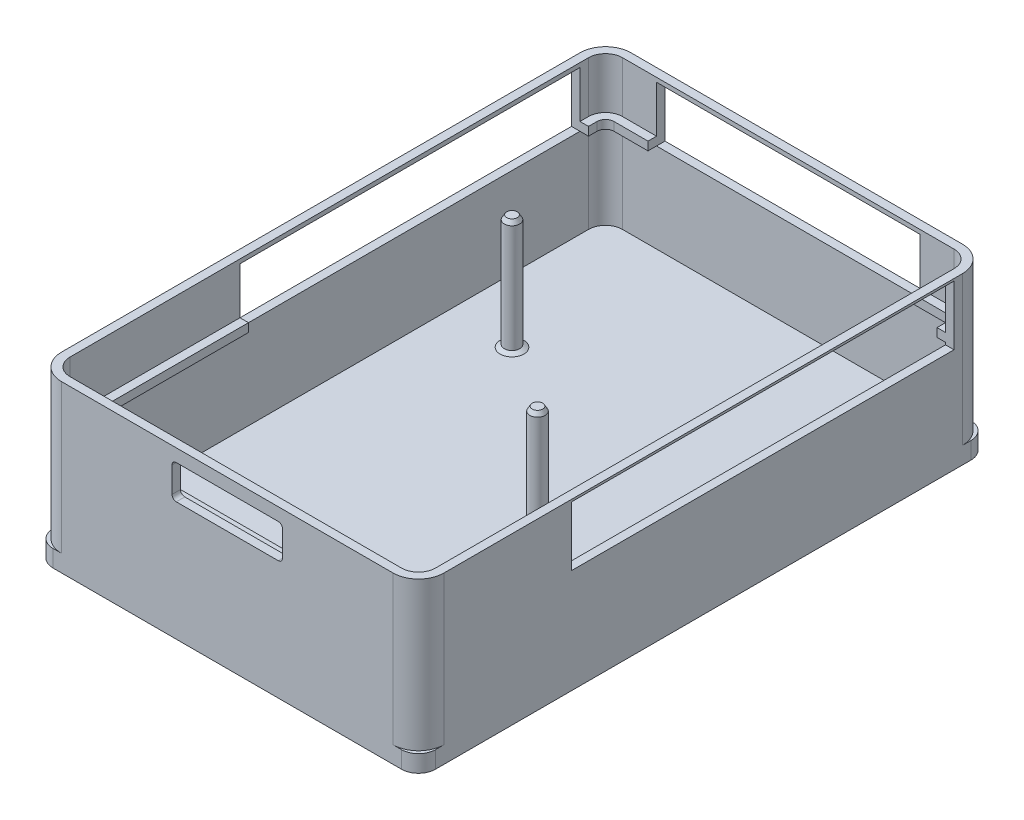
SolidWorks part; units mm, degrees
ref_plane "前视基准面" through (0, 0, 0) normal (0, 0, 1) x (1, 0, 0)
ref_plane "上视基准面" through (0, 0, 0) normal (0, 1, 0) x (1, 0, 0)
ref_plane "右视基准面" through (0, 0, 0) normal (1, 0, 0) x (0, 0, -1)
sketch "草图1" plane through (0, 0, 0) normal (0, 1, 0) x (1, 0, 0)
  line L0 (-22.5, 31.5) -> (-22.5, -31.5)
  line L1 (-20.5, -33.5) -> (20.5, -33.5)
  line L2 (22.5, -31.5) -> (22.5, 31.5)
  line L3 (20.5, 33.5) -> (-20.5, 33.5)
  arc A0 (-22.5, 31.5) -> (-20.5, 33.5) centre (-20.5, 31.5) cw
  arc A1 (22.5, 31.5) -> (20.5, 33.5) centre (20.5, 31.5) ccw
  arc A2 (-20.5, -33.5) -> (-22.5, -31.5) centre (-20.5, -31.5) cw
  arc A3 (20.5, -33.5) -> (22.5, -31.5) centre (20.5, -31.5) ccw
  point P7 (-0.3452, -0.9781)
  point P8 (0, -1.3233)
  point P9 (-22.5, 33.5)
  point P12 (22.5, 33.5)
  point P17 (22.5, -33.5)
  dimension "D5" = 2
  dimension "D6" = 2
  dimension "D7" = 2
  dimension "D8" = 2
  dimension "D1" = 45
  dimension "D2" = 67
  dimension "D3" = 33.5
  dimension "D4" = 22.5
extrude "凸台-拉伸1" add sketch "草图1" along normal blind 2
ref_plane "基准面1" through (0, 2, 0) normal (0, 1, 0) x (1, 0, 0)
sketch "草图2" plane through (0, 2, 0) normal (0, 1, 0) x (1, 0, 0)
  line L0 (-21.5, 30.5) -> (-21.5, -30.5)
  line L1 (-19.5, -32.5) -> (19.5, -32.5)
  line L2 (21.5, -30.5) -> (21.5, 30.5)
  line L3 (19.5, 32.5) -> (-19.5, 32.5)
  line L4 (19.5, 33.5) -> (-19.5, 33.5)
  line L5 (-22.5, 30.5) -> (-22.5, -30.5)
  line L6 (-19.5, -33.5) -> (19.5, -33.5)
  line L7 (22.5, -30.5) -> (22.5, 30.5)
  arc A0 (-21.5, 30.5) -> (-19.5, 32.5) centre (-19.5, 30.5) cw
  arc A1 (-19.5, -32.5) -> (-21.5, -30.5) centre (-19.5, -30.5) cw
  arc A2 (19.5, -32.5) -> (21.5, -30.5) centre (19.5, -30.5) ccw
  arc A3 (21.5, 30.5) -> (19.5, 32.5) centre (19.5, 30.5) ccw
  arc A4 (-22.5, 30.5) -> (-19.5, 33.5) centre (-19.5, 30.5) cw
  arc A5 (-19.5, -33.5) -> (-22.5, -30.5) centre (-19.5, -30.5) cw
  arc A6 (19.5, -33.5) -> (22.5, -30.5) centre (19.5, -30.5) ccw
  arc A7 (22.5, 30.5) -> (19.5, 33.5) centre (19.5, 30.5) ccw
  point P7 (-21.5, 32.5)
  point P12 (21.5, -32.5)
  point P15 (21.5, 32.5)
  dimension "D5" = 2
  dimension "D6" = 2
  dimension "D1" = 43
  dimension "D2" = 65
  dimension "D3" = 32.5
  dimension "D4" = 21.5
  dimension "D7" = 1
extrude "凸台-拉伸2" add sketch "草图2" along normal blind 17.5
sketch "草图3" plane through (0, 2, 0) normal (0, 1, 0) x (1, 0, 0)
  circle A0 centre (-14, 14) radius 0.9
  circle A1 centre (7, -4) radius 0.9
  circle A2 centre (-19, -30) radius 0.9
  point P6 (0, 0)
  point P9 (-12.6689, 9.1344)
  dimension "D3" = 1.8
  dimension "D4" = 1.8
  dimension "D7" = 1.8
  dimension "D1" = 14
  dimension "D2" = 14
  dimension "D5" = 7
  dimension "D6" = 4
  dimension "D8" = 19
  dimension "D9" = 30
extrude "凸台-拉伸3" add sketch "草图3" along normal blind 13.5
chamfer "倒角2" distance 0.5 angle 30 2 edges at (-14, 2, -14.9) (-14, 15.5, -13.1)
chamfer "倒角3" distance 0.5 angle 30 2 edges at (7, 2, 3.1) (7, 15.5, 4.9)
chamfer "倒角4" distance 0.5 angle 30 2 edges at (-19, 2, 29.1) (-19, 15.5, 30.9)
ref_plane "基准面2" through (0, 0, 33.5) normal (0, 0, 1) x (1, 0, 0)
sketch "草图4" plane through (0, 0, 33.5) normal (0, 0, 1) x (1, 0, 0)
  line L0 (-6.5, 17.5) -> (-6.5, 14.5)
  line L1 (-6, 14) -> (6, 14)
  line L2 (6.5, 14.5) -> (6.5, 17.5)
  line L3 (6, 18) -> (-6, 18)
  line L8 (-19.5, 19.5) -> (-19.5, 2) construction
  line L9 (19.5, 19.5) -> (19.5, 2) construction
  line L10 (-19.5, 19.5) -> (19.5, 19.5) construction
  arc A0 (6.5, 17.5) -> (6, 18) centre (6, 17.5) ccw
  arc A1 (6, 14) -> (6.5, 14.5) centre (6, 14.5) ccw
  arc A2 (-6, 14) -> (-6.5, 14.5) centre (-6, 14.5) cw
  arc A3 (-6.5, 17.5) -> (-6, 18) centre (-6, 17.5) cw
  point P12 (6.5, 18)
  point P15 (6.5, 14)
  dimension "D5" = 0.5
  dimension "D1" = 13
  dimension "D2" = 13
  dimension "D3" = 1.5
  dimension "D4" = 4
ref_plane "基准面4" through (0, 12.5, 0) normal (0, 1, 0) x (1, 0, 0)
sketch "草图6" plane through (0, 12.5, 0) normal (0, 1, 0) x (1, 0, 0)
  line L0 (-21.5, 30.5) -> (-21.5, -30.5)
  line L1 (-19.5, -32.5) -> (19.5, -32.5)
  line L2 (21.5, -30.5) -> (21.5, 30.5)
  line L3 (19.5, 32.5) -> (-19.5, 32.5)
  line L4 (19.5, 31.5) -> (-19.5, 31.5)
  line L5 (-20.5, 30.5) -> (-20.5, -30.5)
  line L6 (-19.5, -31.5) -> (19.5, -31.5)
  line L7 (20.5, -30.5) -> (20.5, 30.5)
  arc A0 (-21.5, 30.5) -> (-19.5, 32.5) centre (-19.5, 30.5) cw
  arc A1 (-19.5, -32.5) -> (-21.5, -30.5) centre (-19.5, -30.5) cw
  arc A2 (19.5, -32.5) -> (21.5, -30.5) centre (19.5, -30.5) ccw
  arc A3 (21.5, 30.5) -> (19.5, 32.5) centre (19.5, 30.5) ccw
  arc A4 (-20.5, 30.5) -> (-19.5, 31.5) centre (-19.5, 30.5) cw
  arc A5 (-19.5, -31.5) -> (-20.5, -30.5) centre (-19.5, -30.5) cw
  arc A6 (19.5, -31.5) -> (20.5, -30.5) centre (19.5, -30.5) ccw
  arc A7 (20.5, 30.5) -> (19.5, 31.5) centre (19.5, 30.5) ccw
  point P9 (-21.5, -32.5)
  point P12 (21.5, -32.5)
  point P15 (21.5, 32.5)
  dimension "D5" = 2
  dimension "D6" = 2
  dimension "D1" = 43
  dimension "D2" = 65
  dimension "D3" = 32.5
  dimension "D4" = 21.5
  dimension "D7" = 1
extrude "凸台-拉伸5" add sketch "草图6" along normal blind 1
extrude "切除-拉伸1" cut sketch "草图4" against normal up to next
sketch "草图7" plane through (22.5, 0, 0) normal (1, 0, 0) x (0, 0, -1)
  line L1 (-15.5, 12.2388) -> (-15.5, 19.2388)
  line L2 (-15.5, 19.2388) -> (29.5, 19.2388)
  line L3 (29.5, 19.2388) -> (29.5, 12.2388)
  line L4 (29.5, 12.2388) -> (-15.5, 12.2388)
  line L6 (-30.5, 19.5) -> (-30.5, 2) construction
  dimension "D1" = 7
  dimension "D2" = 15
  dimension "D3" = 45
extrude "切除-拉伸2" cut sketch "草图7" against normal up to next
sketch "草图8" plane through (-22.5, 0, 0) normal (-1, 0, 0) x (0, 0, 1)
  line L0 (-29.5, 19) -> (-29.5, 12.5)
  line L1 (23.65, 12.5) -> (-23.65, 12.5) construction
  line L2 (-29.5, 12.5) -> (10.5, 12.5)
  line L3 (10.5, 12.5) -> (10.5, 15.0141)
  line L4 (10.5, 15.0141) -> (10.5, 19)
  line L5 (10.5, 19) -> (-29.5, 19)
  line L6 (-30.5, 19.5) -> (-30.5, 2) construction
  line L7 (30.5, 19.5) -> (30.5, 2) construction
  dimension "D1" = 1
  dimension "D2" = 20
  dimension "D3" = 6.5
extrude "切除-拉伸3" cut sketch "草图8" against normal up to next
sketch "草图9" plane through (0, 0, -33.5) normal (0, 0, -1) x (-1, 0, 0)
  line L0 (-15.5, 19) -> (-15.5, 12.5)
  line L1 (23.65, 12.5) -> (-23.65, 12.5) construction
  line L2 (-15.5, 12.5) -> (15.5, 12.5)
  line L3 (15.5, 12.5) -> (15.5, 19)
  line L4 (15.5, 19) -> (-15.5, 19)
  line L5 (-19.5, 19.5) -> (-19.5, 2) construction
  line L6 (19.5, 19.5) -> (19.5, 2) construction
  dimension "D1" = 4
  dimension "D2" = 4
  dimension "D3" = 6.5
extrude "切除-拉伸4" cut sketch "草图9" against normal up to next
